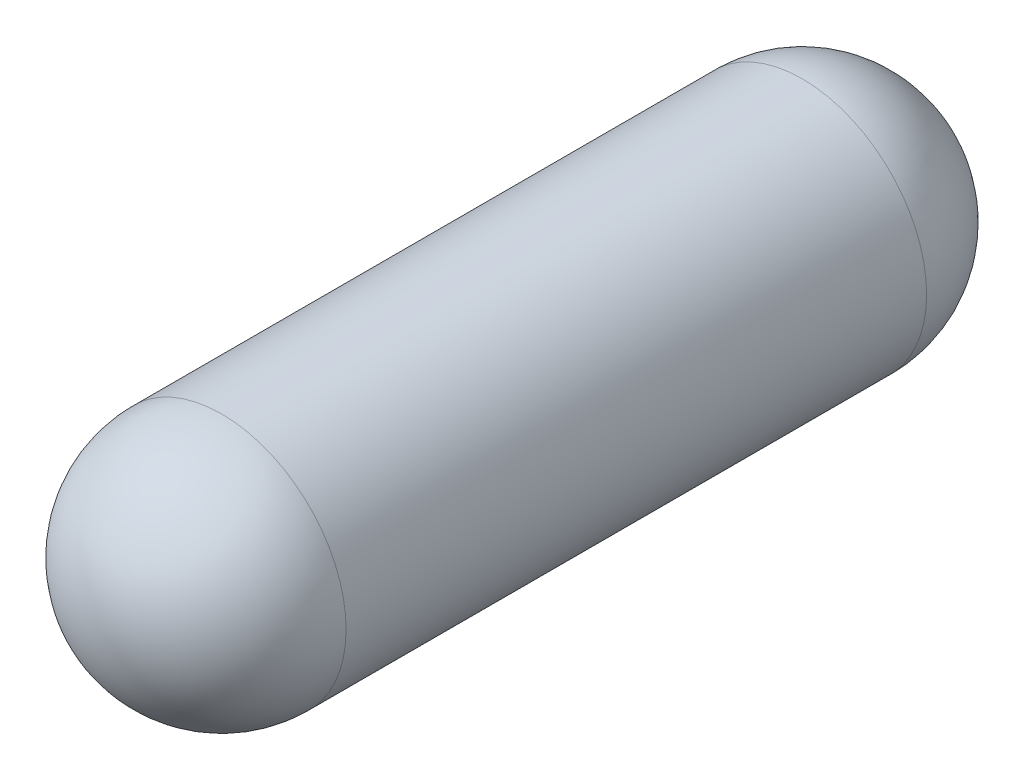
SolidWorks part; units mm, degrees
material "Acero al carbono fundido"
ref_plane "Front" through (0, 0, 0) normal (0, 0, 1) x (1, 0, 0)
ref_plane "Top" through (0, 0, 0) normal (0, 1, 0) x (1, 0, 0)
ref_plane "Right" through (0, 0, 0) normal (1, 0, 0) x (0, 0, -1)
sketch "Croquis1" plane through (0, 0, 0) normal (0, 0, 1) x (1, 0, 0)
  circle A0 centre (0, 0) radius 3
  dimension "D1" = 6
extrude "Saliente-Extruir1" add sketch "Croquis1" along normal blind 20
fillet "Redondeo1" radius 3 2 edges at (3, 0, 0) (3, 0, 20)
